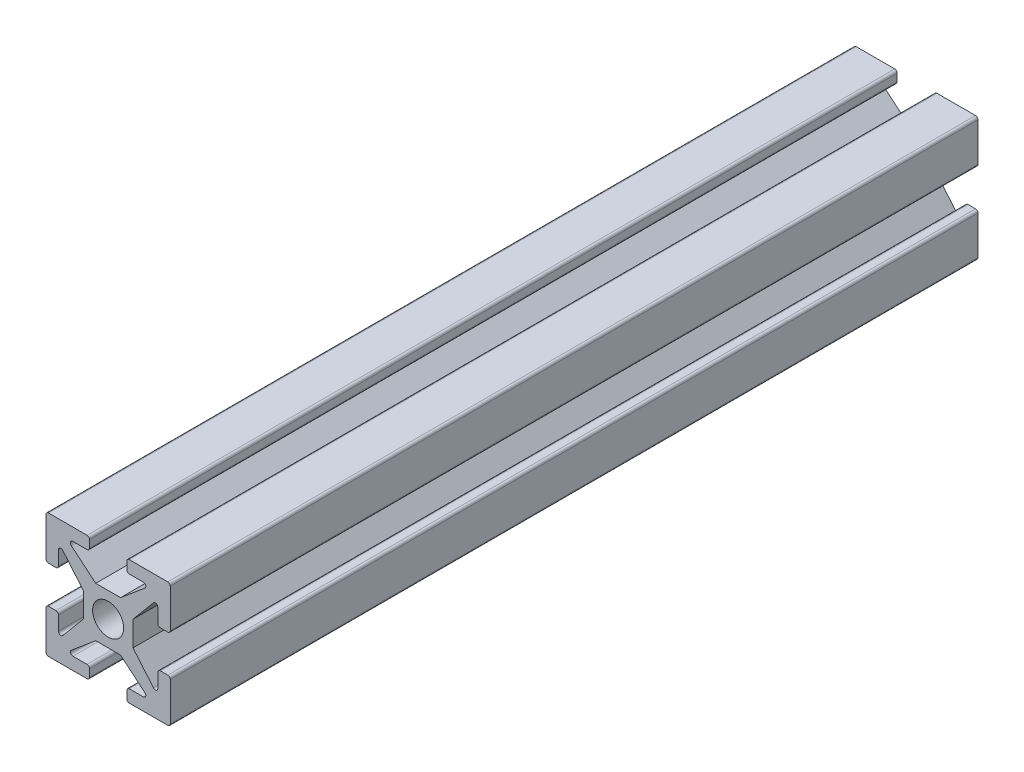
SolidWorks part; units mm, degrees
ref_plane "Front Plane" through (0, 0, 0) normal (0, 0, 1) x (1, 0, 0)
ref_plane "Top Plane" through (0, 0, 0) normal (0, 1, 0) x (1, 0, 0)
ref_plane "Right Plane" through (0, 0, 0) normal (1, 0, 0) x (0, 0, -1)
sketch "Sketch1" plane through (0, 0, 0) normal (0, 0, 1) x (1, 0, 0)
  line L0 (0, 2) -> (0, -2) construction
  line L1 (2.4868, 1) -> (2, 1) construction
  line L2 (2.4868, 1) -> (2.4868, -1) construction
  line L3 (-4.8, 5) -> (-1.7, 5)
  line L4 (2, 2) -> (0, 0) construction
  line L5 (5, 5) -> (0, 0) construction
  line L6 (-5, 5) -> (0, 0) construction
  line L7 (5, 1.7) -> (5, 4.8)
  line L8 (-2, -1) -> (-2, 1)
  line L9 (-1, 2) -> (1, 2)
  line L10 (1, 2) -> (2.9626, 3.6468)
  line L11 (2, 1) -> (3.6468, 2.9626)
  line L12 (-2, 2) -> (0, 0) construction
  line L13 (2.834, 4) -> (1.7, 4)
  line L14 (-5, 0) -> (5, 0) construction
  line L15 (-4, 1.7) -> (-4, 2.834)
  line L16 (-5, 5) -> (-1.5, 5)
  line L17 (-5, 5) -> (-5, 1.5)
  line L18 (-4.8, 1.5) -> (-4.2, 1.5)
  line L19 (-1.5, 4.8) -> (-1.5, 4.2)
  line L20 (-2.834, 4) -> (-1.7, 4)
  line L21 (-2.4868, 1) -> (-2.4868, -1) construction
  line L22 (1.5, 4.8) -> (1.5, 4.2)
  line L23 (-2, 1) -> (-3.6468, 2.9626)
  line L24 (-2.4868, 1) -> (-2, 1) construction
  line L25 (-1, 2) -> (-2.9626, 3.6468)
  line L26 (4.8, 1.5) -> (4.2, 1.5)
  line L27 (-5, 1.7) -> (-5, 4.8)
  line L28 (5, 5) -> (5, 1.5)
  line L29 (5, 5) -> (1.5, 5)
  line L30 (4, 1.7) -> (4, 2.834)
  line L31 (2, -1) -> (2, 1)
  line L32 (4.8, 5) -> (1.7, 5)
  line L33 (-2.4868, -1) -> (-2, -1) construction
  line L34 (-2, -2) -> (0, 0) construction
  line L35 (-5, -5) -> (0, 0) construction
  line L36 (5, -5) -> (0, 0) construction
  line L37 (2, -2) -> (0, 0) construction
  line L38 (2.4868, -1) -> (2, -1) construction
  line L39 (4.8, -5) -> (1.7, -5)
  line L40 (4, -1.7) -> (4, -2.834)
  line L41 (5, -5) -> (1.5, -5)
  line L42 (5, -5) -> (5, -1.5)
  line L43 (-5, -1.7) -> (-5, -4.8)
  line L44 (4.8, -1.5) -> (4.2, -1.5)
  line L45 (-1, -2) -> (-2.9626, -3.6468)
  line L46 (-2, -1) -> (-3.6468, -2.9626)
  line L47 (1.5, -4.8) -> (1.5, -4.2)
  line L48 (-2.834, -4) -> (-1.7, -4)
  line L49 (-1.5, -4.8) -> (-1.5, -4.2)
  line L50 (-4.8, -1.5) -> (-4.2, -1.5)
  line L51 (-5, -5) -> (-5, -1.5)
  line L52 (-5, -5) -> (-1.5, -5)
  line L53 (-4, -1.7) -> (-4, -2.834)
  line L54 (2.834, -4) -> (1.7, -4)
  line L55 (2, -1) -> (3.6468, -2.9626)
  line L56 (1, -2) -> (2.9626, -3.6468)
  line L57 (-1, -2) -> (1, -2)
  line L58 (5, -1.7) -> (5, -4.8)
  line L59 (-4.8, -5) -> (-1.7, -5)
  circle A0 centre (0, 0) radius 1.25
  arc A1 (-2.9626, 3.6468) -> (-2.834, 4) centre (-2.834, 3.8) cw
  arc A2 (-3.6468, 2.9626) -> (-4, 2.834) centre (-3.8, 2.834) ccw
  arc A3 (-1.7, 4) -> (-1.5, 4.2) centre (-1.7, 4.2) ccw
  arc A4 (-4, 1.7) -> (-4.2, 1.5) centre (-4.2, 1.7) cw
  arc A5 (-1.7, 5) -> (-1.5, 4.8) centre (-1.7, 4.8) cw
  arc A6 (-5, 1.7) -> (-4.8, 1.5) centre (-4.8, 1.7) ccw
  arc A7 (-5, 4.8) -> (-4.8, 5) centre (-4.8, 4.8) cw
  arc A8 (5, 4.8) -> (4.8, 5) centre (4.8, 4.8) ccw
  arc A9 (5, 1.7) -> (4.8, 1.5) centre (4.8, 1.7) cw
  arc A10 (1.7, 5) -> (1.5, 4.8) centre (1.7, 4.8) ccw
  arc A11 (4, 1.7) -> (4.2, 1.5) centre (4.2, 1.7) ccw
  arc A12 (1.7, 4) -> (1.5, 4.2) centre (1.7, 4.2) cw
  arc A13 (3.6468, 2.9626) -> (4, 2.834) centre (3.8, 2.834) cw
  arc A14 (2.9626, 3.6468) -> (2.834, 4) centre (2.834, 3.8) ccw
  arc A15 (2.9626, -3.6468) -> (2.834, -4) centre (2.834, -3.8) cw
  arc A16 (3.6468, -2.9626) -> (4, -2.834) centre (3.8, -2.834) ccw
  arc A17 (1.7, -4) -> (1.5, -4.2) centre (1.7, -4.2) ccw
  arc A18 (4, -1.7) -> (4.2, -1.5) centre (4.2, -1.7) cw
  arc A19 (1.7, -5) -> (1.5, -4.8) centre (1.7, -4.8) cw
  arc A20 (5, -1.7) -> (4.8, -1.5) centre (4.8, -1.7) ccw
  arc A21 (5, -4.8) -> (4.8, -5) centre (4.8, -4.8) cw
  arc A22 (-5, -4.8) -> (-4.8, -5) centre (-4.8, -4.8) ccw
  arc A23 (-5, -1.7) -> (-4.8, -1.5) centre (-4.8, -1.7) cw
  arc A24 (-1.7, -5) -> (-1.5, -4.8) centre (-1.7, -4.8) ccw
  arc A25 (-4, -1.7) -> (-4.2, -1.5) centre (-4.2, -1.7) ccw
  arc A26 (-1.7, -4) -> (-1.5, -4.2) centre (-1.7, -4.2) cw
  arc A27 (-3.6468, -2.9626) -> (-4, -2.834) centre (-3.8, -2.834) cw
  arc A28 (-2.9626, -3.6468) -> (-2.834, -4) centre (-2.834, -3.8) ccw
  point P0 (0, 0)
  point P4 (-3.3835, 4)
  point P6 (0, 0)
  point P7 (2, 0)
  point P10 (3.3835, -4)
  point P14 (-4, 3.3835)
  point P71 (4, 3.3835)
  point P72 (3.3835, 4)
  point P75 (-2.4868, 0)
  point P80 (2.4868, 0)
  point P129 (-2, 0)
  point P130 (4, -3.3835)
  point P131 (-4, -3.3835)
  point P132 (-3.3835, -4)
  dimension "D5" = 2.5
  dimension "D2" = 0.2
  dimension "D6" = 1.5
  dimension "D8" = 1
  dimension "D10" = 50
extrude "Boss-Extrude1" add sketch "Sketch1" along normal blind 65 contours A28 L45 L57 L56 A15 L54 A17 L47 A19 L39 A21 L42 A20 L44 A18 L40 A16 L55 L31 L11 A13 L30 A11 L26 A9 L7 A8 L29 A10 L22 A12 L13 A14 L10 L9 L25 A1 L20 A3 L19 A5 L3 A7 L17 A6 L18 A4 L15 A2 L23 L8
